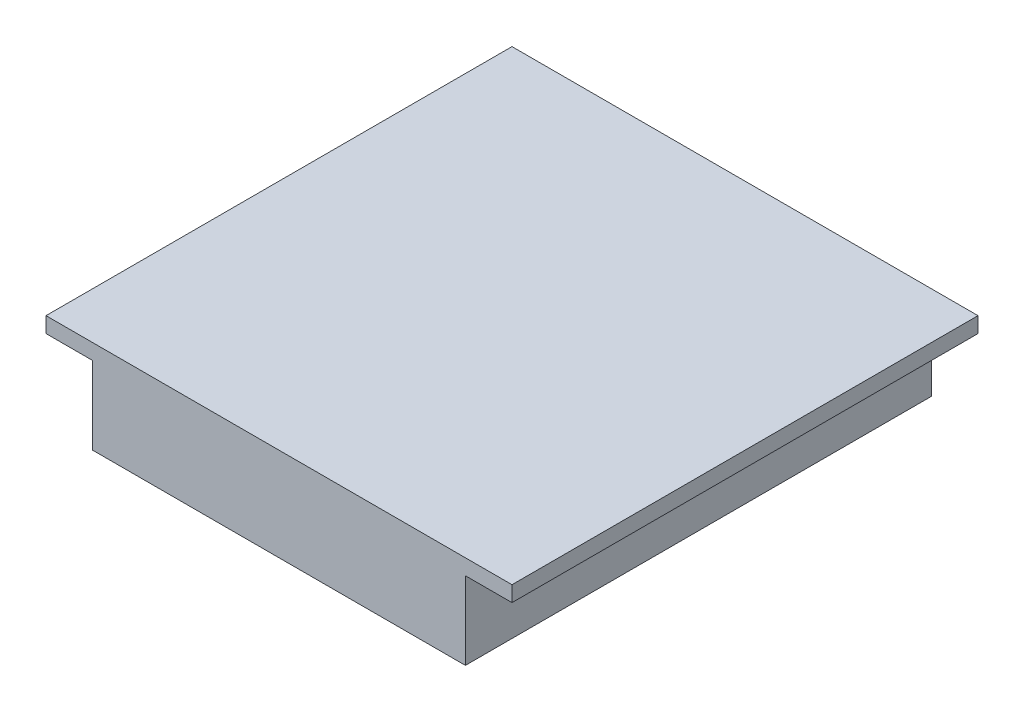
SolidWorks part; units mm, degrees
ref_plane "Front Plane" through (0, 0, 0) normal (0, 0, 1) x (1, 0, 0)
ref_plane "Top Plane" through (0, 0, 0) normal (0, 1, 0) x (1, 0, 0)
ref_plane "Right Plane" through (0, 0, 0) normal (1, 0, 0) x (0, 0, -1)
sketch "Sketch1" plane through (0, 0, 0) normal (0, 0, 1) x (1, 0, 0)
  line L0 (-59.5829, 25) -> (-44.5829, 25)
  line L1 (-44.5829, 25) -> (-44.5829, 0)
  line L2 (-44.5829, 0) -> (75.4171, 0)
  line L3 (75.4171, 0) -> (75.4171, 25)
  line L4 (75.4171, 25) -> (90.4171, 25)
  line L5 (-59.5829, 25) -> (-59.5829, 30)
  line L6 (-59.5829, 30) -> (90.4171, 30)
  line L7 (90.4171, 30) -> (90.4171, 25)
  dimension "D1" = 150
  dimension "D2" = 120
  dimension "D3" = 15
  dimension "D4" = 30
  dimension "D5" = 5
  dimension "D6" = 5
extrude "Boss-Extrude1" add sketch "Sketch1" along normal blind 150
